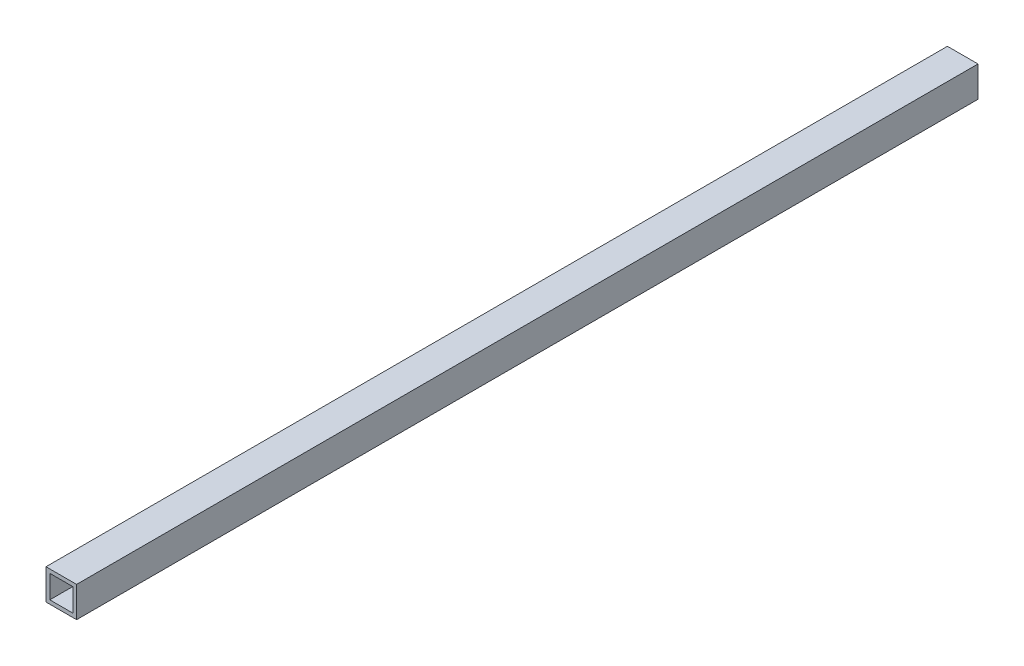
SolidWorks part; units mm, degrees
ref_plane "Front Plane" through (0, 0, 0) normal (0, 0, 1) x (1, 0, 0)
ref_plane "Top Plane" through (0, 0, 0) normal (0, 1, 0) x (1, 0, 0)
ref_plane "Right Plane" through (0, 0, 0) normal (1, 0, 0) x (0, 0, -1)
sketch "Sketch1" plane through (0, 0, 0) normal (0, 1, 0) x (1, 0, 0)
  line L0 (-347.5071, -311.6059) -> (-296.7071, -399.5941) construction
  line L1 (376.3929, -304.8) -> (376.3929, 374.1941) construction
  line L2 (-347.5071, -311.6059) -> (-347.5071, 374.1941) construction
  line L3 (-347.5071, 374.1941) -> (-322.1071, 374.1941) construction
  line L4 (336.3282, -374.1941) -> (376.3929, -304.8) construction
  line L5 (-347.5071, 374.1941) -> (401.7929, 374.1941) construction
  line L6 (-347.5071, 374.1941) -> (-347.5071, 399.5941) construction
  line L7 (-347.5071, 399.5941) -> (401.7929, 399.5941) construction
  line L8 (401.7929, 374.1941) -> (401.7929, 399.5941) construction
  line L9 (-296.7071, -399.5941) -> (350.9929, -399.5941) construction
  line L10 (350.9929, -399.5941) -> (401.7929, -311.6059) construction
  line L11 (401.7929, -311.6059) -> (401.7929, 374.1941) construction
  line L12 (-282.0424, -374.1941) -> (336.3282, -374.1941) construction
  line L13 (-322.1071, -304.8) -> (-282.0424, -374.1941) construction
  line L14 (-322.1071, -304.8) -> (-322.1071, 374.1941) construction
  line L15 (0, 374.1941) -> (0, -374.1941)
  line L16 (-25.4, 374.1941) -> (-25.4, -374.1941)
  line L17 (-25.4, 374.1941) -> (0, 374.1941)
  line L18 (-25.4, -374.1941) -> (0, -374.1941)
  dimension "D1" = 685.8
  dimension "D2" = 25.4
  dimension "D3" = 749.3
  dimension "D4" = 25.4
  dimension "D5" = 101.6
  dimension "D6" = 647.7
  dimension "D7" = 685.8
  dimension "D8" = 101.6
  dimension "D9" = 25.4
  dimension "D10" = 25.4
extrude "Boss-Extrude1" add sketch "Sketch1" along normal blind 25.4
sketch "Sketch2" plane through (0, 0, 374.1941) normal (0, 0, 1) x (1, 0, 0)
  line L0 (-25.4, 25.4) -> (0, 25.4) construction
  line L1 (-3.175, 3.175) -> (-22.225, 3.175)
  line L2 (-3.175, 3.175) -> (-3.175, 22.225)
  line L3 (-3.175, 22.225) -> (-22.225, 22.225)
  line L4 (-22.225, 3.175) -> (-22.225, 22.225)
  line L5 (-3.175, 3.175) -> (-22.225, 22.225) construction
  line L6 (-3.175, 22.225) -> (-22.225, 3.175) construction
  line L7 (-25.4, 25.4) -> (-25.4, 0) construction
  line L8 (-25.4, 0) -> (0, 0) construction
  line L9 (0, 25.4) -> (0, 0) construction
  point P0 (-12.7, 12.7)
  dimension "D1" = 3.175
  dimension "D2" = 3.175
  dimension "D3" = 3.175
  dimension "D4" = 3.175
extrude "Cut-Extrude1" cut sketch "Sketch2" against normal through all
